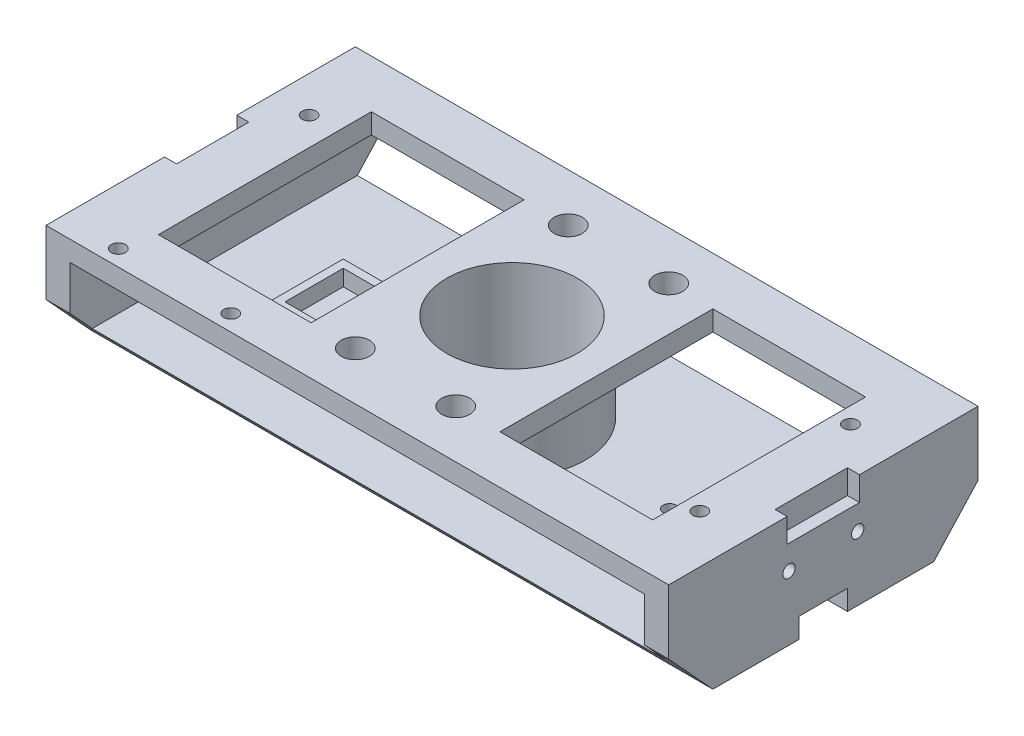
SolidWorks part; units mm, degrees
ref_plane "Front Plane" through (0, 0, 0) normal (0, 0, 1) x (1, 0, 0)
ref_plane "Top Plane" through (0, 0, 0) normal (0, 1, 0) x (1, 0, 0)
ref_plane "Right Plane" through (0, 0, 0) normal (1, 0, 0) x (0, 0, -1)
sketch "Sketch3" plane through (0, 0, 0) normal (0, 1, 0) x (1, 0, 0)
  line L1 (-77.5, 38.5) -> (77.5, 38.5)
  line L2 (-77.5, 38.5) -> (-77.5, -38.5)
  line L3 (-77.5, -38.5) -> (77.5, -38.5)
  line L4 (77.5, 38.5) -> (77.5, -38.5)
  line L5 (-77.5, 38.5) -> (77.5, -38.5) construction
  line L6 (-77.5, -38.5) -> (77.5, 38.5) construction
  point P0 (0, 0)
  dimension "D1" = 155
  dimension "D2" = 77
extrude "Boss-Extrude1" add sketch "Sketch3" along normal blind 28
sketch "Sketch5" plane through (0, 0, 38.5) normal (0, 0, 1) x (1, 0, 0)
  line L0 (-77.5, 28) -> (77.5, 28) construction
  line L1 (-71.5, 23) -> (71.5, 23)
  line L2 (-71.5, 23) -> (-71.5, 6)
  line L3 (-71.5, 6) -> (71.5, 6)
  line L4 (71.5, 23) -> (71.5, 6)
  line L5 (-77.5, 0) -> (77.5, 0) construction
  line L6 (77.5, 28) -> (77.5, 0) construction
  line L7 (-77.5, 28) -> (-77.5, 0) construction
  dimension "D1" = 5
  dimension "D2" = 6
  dimension "D3" = 6
  dimension "D4" = 6
extrude "Cut-Extrude1" cut sketch "Sketch5" against normal through all
sketch "Sketch12" plane through (0, 6, 0) normal (0, 1, 0) x (1, 0, 0)
  circle A0 centre (0, 0) radius 18.25
  dimension "D1" = 36.5
extrude "Boss-Extrude3" add sketch "Sketch12" along normal up to next
sketch "Sketch15" plane through (0, 28, 0) normal (0, 1, 0) x (1, 0, 0)
  circle A0 centre (0, 0) radius 16.25
  circle A1 centre (0, 0) radius 18.25 construction
  dimension "D1" = 2
extrude "Cut-Extrude4" cut sketch "Sketch15" against normal offset from surface (27 mm away) 1 up to face at (0, 0, 0)
sketch "Sketch16" plane through (0, 28, 0) normal (0, 1, 0) x (1, 0, 0)
  line L0 (77.5, 38.5) -> (-77.5, 38.5) construction
  line L1 (-61.5, 26.5) -> (-23.5, 26.5)
  line L2 (-61.5, 26.5) -> (-61.5, -26.5)
  line L3 (-61.5, -26.5) -> (-23.5, -26.5)
  line L4 (-23.5, 26.5) -> (-23.5, -26.5)
  line L5 (23.5, 26.5) -> (61.5, 26.5)
  line L6 (23.5, 26.5) -> (23.5, -26.5)
  line L7 (23.5, -26.5) -> (61.5, -26.5)
  line L8 (61.5, 26.5) -> (61.5, -26.5)
  line L9 (-77.5, -38.5) -> (77.5, -38.5) construction
  line L10 (77.5, -38.5) -> (77.5, 38.5) construction
  line L11 (-77.5, 38.5) -> (-77.5, -38.5) construction
  line L12 (-23.5, 26.5) -> (23.5, 26.5) construction
  line L15 (-77.5, 0) -> (77.5, 0) construction
  line L16 (0, 38.5) -> (0, -38.5) construction
  circle A2 centre (0, 0) radius 16.25 construction
  circle A3 centre (-12.5, 26.5) radius 3.5
  circle A4 centre (12.5, 26.5) radius 3.5
  circle A5 centre (12.5, -26.5) radius 3.5
  circle A6 centre (-12.5, -26.5) radius 3.5
  dimension "D9" = 7
  dimension "D1" = 12
  dimension "D2" = 12
  dimension "D3" = 16
  dimension "D4" = 12
  dimension "D5" = 12
  dimension "D6" = 16
  dimension "D7" = 23.5
  dimension "D8" = 23.5
  dimension "D10" = 7.5
extrude "Cut-Extrude5" cut sketch "Sketch16" against normal up to next
sketch "Sketch19" plane through (0, 0, 0) normal (0, -1, 0) x (1, 0, 0)
  line L0 (-77.5, -38.5) -> (-77.5, 38.5) construction
  line L1 (-77.5, 6) -> (-67.5, 6)
  line L2 (-77.5, 6) -> (-77.5, -6)
  line L3 (-77.5, -6) -> (-67.5, -6)
  line L4 (-67.5, 6) -> (-67.5, -6)
  line L5 (0, 38.5) -> (0, -38.5) construction
  line L6 (-77.5, 38.5) -> (77.5, 38.5) construction
  line L7 (77.5, -38.5) -> (-77.5, -38.5) construction
  line L8 (77.5, -6) -> (67.5, -6)
  line L9 (67.5, 6) -> (67.5, -6)
  line L10 (77.5, 6) -> (67.5, 6)
  line L11 (77.5, 6) -> (77.5, -6)
  point P7 (-77.5, 0)
  dimension "D1" = 10
  dimension "D2" = 12
extrude "Cut-Extrude6" cut sketch "Sketch19" against normal blind 5
sketch "Sketch22" plane through (-77.5, 0, 0) normal (-1, 0, 0) x (0, 0, 1)
  line L0 (-38.5, 0) -> (-38.5, 12)
  line L1 (-38.5, 28) -> (-38.5, 0) construction
  line L2 (-38.5, 12) -> (-27.5, 0)
  line L3 (-38.5, 0) -> (-6, 0) construction
  line L4 (-27.5, 0) -> (-38.5, 0)
  line L5 (0, 0) -> (0, 38.6844) construction
  line L6 (38.5, 12) -> (27.5, 0)
  line L7 (38.5, 0) -> (38.5, 12)
  line L8 (27.5, 0) -> (38.5, 0)
  dimension "D2" = 12
  dimension "D1" = 27.5
extrude "Cut-Extrude7" cut sketch "Sketch22" against normal through all
sketch "Sketch23" plane through (0, 0, 0) normal (0, -1, 0) x (1, 0, 0)
  line L0 (0, 0) -> (0, 26.8111) construction
  circle A1 centre (39.25, 0) radius 1.625
  circle A2 centre (-39.25, 0) radius 1.625
  dimension "D1" = 39.25
  dimension "D2" = 3.25
extrude "Cut-Extrude8" cut sketch "Sketch23" against normal up to next
sketch "Sketch28" plane through (0, 6, 0) normal (0, 1, 0) x (1, 0, 0)
  line L1 (-51.25, 9.25) -> (-27.25, 9.25)
  line L2 (-51.25, 9.25) -> (-51.25, -9.25)
  line L3 (-51.25, -9.25) -> (-27.25, -9.25)
  line L4 (-27.25, 9.25) -> (-27.25, -9.25)
  line L5 (-51.25, 9.25) -> (-27.25, -9.25) construction
  line L6 (-51.25, -9.25) -> (-27.25, 9.25) construction
  point P0 (-39.25, 0)
  dimension "D1" = 24
  dimension "D2" = 18.5
extrude "Boss-Extrude4" add sketch "Sketch28" along normal blind 4
sketch "Sketch29" plane through (0, 10, 0) normal (0, 1, 0) x (1, 0, 0)
  line L0 (-27.25, 9.25) -> (-51.25, 9.25) construction
  line L1 (-49.25, 7.25) -> (-29.25, 7.25)
  line L2 (-49.25, 7.25) -> (-49.25, -7.25)
  line L3 (-49.25, -7.25) -> (-29.25, -7.25)
  line L4 (-29.25, 7.25) -> (-29.25, -7.25)
  line L5 (-49.25, 7.25) -> (-29.25, -7.25) construction
  line L6 (-49.25, -7.25) -> (-29.25, 7.25) construction
  line L7 (-51.25, -9.25) -> (-27.25, -9.25) construction
  line L8 (-27.25, -9.25) -> (-27.25, 9.25) construction
  line L9 (-51.25, 9.25) -> (-51.25, -9.25) construction
  point P0 (-39.25, 0)
  dimension "D1" = 2
  dimension "D2" = 2
  dimension "D3" = 2
  dimension "D4" = 2
extrude "Cut-Extrude11" cut sketch "Sketch29" against normal blind 4
sketch "Sketch30" plane through (0, 6, 0) normal (0, 1, 0) x (1, 0, 0)
  circle A0 centre (-39.25, 0) radius 3.25
  circle A1 centre (-39.25, 0) radius 1.625 construction
  dimension "D1" = 6.5
extrude "Cut-Extrude12" cut sketch "Sketch30" against normal blind 1.5
sketch "Sketch31" plane through (77.5, 0, 0) normal (1, 0, 0) x (0, 0, -1)
  line L1 (-27.5, 0) -> (-6, 0) construction
  line L2 (0, 0) -> (0, 28) construction
  line L3 (-38.5, 28) -> (38.5, 28) construction
  circle A0 centre (-8.55, 16) radius 1.55
  circle A1 centre (8.55, 16) radius 1.55
  dimension "D1" = 16
  dimension "D2" = 3.1
  dimension "D3" = 7
extrude "Cut-Extrude13" cut sketch "Sketch31" against normal up to next
sketch "Sketch32" plane through (-77.5, 0, 0) normal (-1, 0, 0) x (0, 0, 1)
  line L0 (0, 0) -> (0, 28) construction
  line L1 (-38.5, 28) -> (38.5, 28) construction
  line L2 (-27.5, 0) -> (-6, 0) construction
  circle A0 centre (-8.55, 16) radius 1.55
  circle A1 centre (8.55, 16) radius 1.55
  dimension "D1" = 3.1
  dimension "D2" = 16
  dimension "D3" = 7
extrude "Cut-Extrude14" cut sketch "Sketch32" against normal up to next
sketch "Sketch33" plane through (-77.5, 0, 0) normal (-1, 0, 0) x (0, 0, 1)
  line L1 (-9, 22) -> (9, 22)
  line L2 (-9, 22) -> (-9, 28)
  line L3 (-9, 28) -> (9, 28)
  line L4 (9, 22) -> (9, 28)
  line L5 (-9, 22) -> (9, 28) construction
  line L6 (-9, 28) -> (9, 22) construction
  line L7 (-38.5, 28) -> (38.5, 28) construction
  circle A0 centre (8.55, 16) radius 1.55 construction
  point P0 (0, 25)
  point P5 (0, 0)
  dimension "D1" = 6
  dimension "D2" = 18
extrude "Cut-Extrude15" cut sketch "Sketch33" against normal blind 3
sketch "Sketch34" plane through (77.5, 0, 0) normal (1, 0, 0) x (0, 0, -1)
  line L0 (-38.5, 28) -> (38.5, 28) construction
  line L1 (-9, 28) -> (9, 28)
  line L2 (-9, 28) -> (-9, 22)
  line L3 (-9, 22) -> (9, 22)
  line L4 (9, 28) -> (9, 22)
  line L5 (-9, 28) -> (9, 22) construction
  line L6 (-9, 22) -> (9, 28) construction
  circle A0 centre (8.55, 16) radius 1.55 construction
  point P0 (0, 25)
  point P5 (0, 0)
  dimension "D1" = 6
  dimension "D2" = 18
extrude "Cut-Extrude16" cut sketch "Sketch34" against normal blind 3
sketch "Sketch35" plane through (0, 6, 0) normal (0, 1, 0) x (1, 0, 0)
  line L2 (71.5, 33) -> (71.5, -33) construction
  circle A0 centre (62.75, 0) radius 3.75
  point P2 (0, 0)
  dimension "D1" = 7.5
  dimension "D2" = 5
extrude "Cut-Extrude17" cut sketch "Sketch35" against normal through all
sketch "Sketch36" plane through (0, 28, 0) normal (0, 1, 0) x (1, 0, 0)
  line L0 (-77.5, -9) -> (-77.5, -38.5) construction
  line L2 (-77.5, -38.5) -> (77.5, -38.5) construction
  line L5 (65.5, -18.75) -> (65.5, -38.5) construction
  line L6 (65.5, 18.75) -> (65.5, 38.5) construction
  line L7 (77.5, 38.5) -> (-77.5, 38.5) construction
  line L8 (77.5, -38.5) -> (77.5, -9) construction
  circle A0 centre (-63.5, -34.5) radius 1.75
  circle A1 centre (-68.5, 18) radius 1.75
  circle A2 centre (-35.5, -34.5) radius 1.75
  circle A3 centre (65.5, -18.75) radius 1.75
  circle A4 centre (65.5, 18.75) radius 1.75
  dimension "D5" = 3.5
  dimension "D6" = 3.5
  dimension "D8" = 3.5
  dimension "D9" = 3.5
  dimension "D10" = 3.5
  dimension "D1" = 14
  dimension "D3" = 52.5
  dimension "D4" = 4
  dimension "D7" = 28
  dimension "D11" = 37.5
  dimension "D12" = 12
  dimension "D2" = 5
extrude "Cut-Extrude18" cut sketch "Sketch36" against normal up to next
equation "\"D4@Sketch16\"=\"D1@Sketch16\""
equation "\"D5@Sketch16\"=\"D1@Sketch16\""
equation "\"D6@Sketch16\"=\"D3@Sketch16\""
equation "\"D2@Sketch16\"=\"D1@Sketch16\""
equation "\"D8@Sketch16\"=\"D7@Sketch16\""
equation "\"D1@Sketch22\"=55/2"
equation "\"D2@Sketch29\"=\"D1@Sketch29\""
equation "\"D3@Sketch29\"=\"D1@Sketch29\""
equation "\"D4@Sketch29\"=\"D1@Sketch29\""
equation "\"D6@Sketch36\"=\"D5@Sketch36\""
equation "\"D8@Sketch36\"=\"D5@Sketch36\""
equation "\"D9@Sketch36\"=\"D5@Sketch36\""
equation "\"D10@Sketch36\"=\"D9@Sketch36\""
